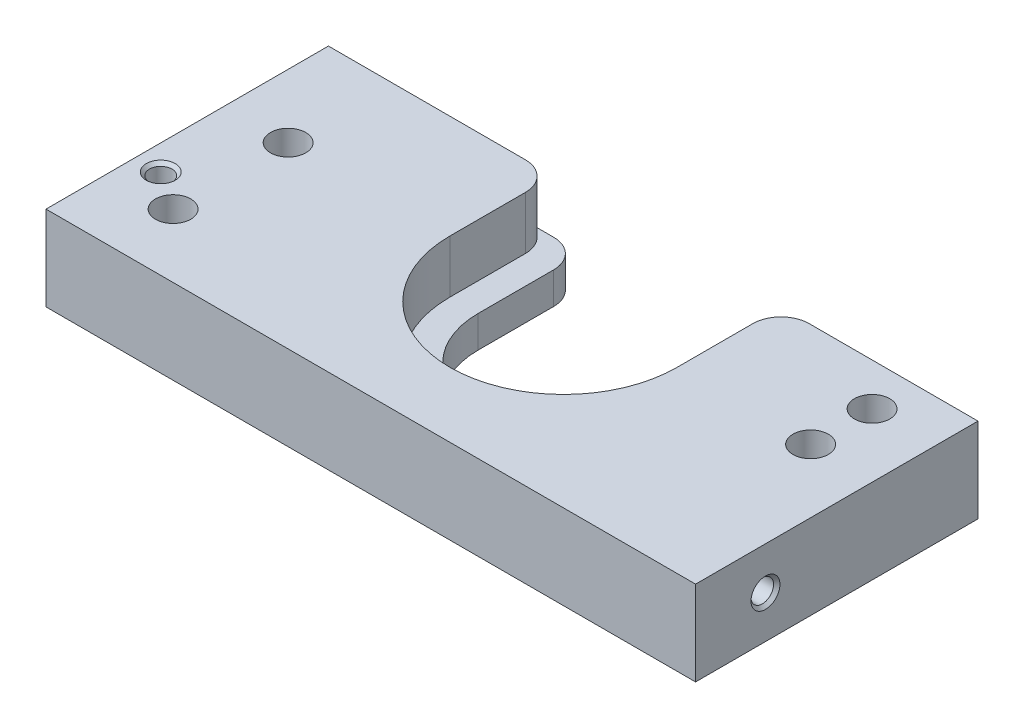
SolidWorks part; units mm, degrees
material "7075-T6, Plate (SS)"
ref_plane "Front" through (0, 0, 0) normal (0, 0, 1) x (1, 0, 0)
ref_plane "Top" through (0, 0, 0) normal (0, 1, 0) x (1, 0, 0)
ref_plane "Right" through (0, 0, 0) normal (1, 0, 0) x (0, 0, -1)
sketch "Sketch2" plane through (0, 0, 0) normal (0, 1, 0) x (1, 0, 0)
  line L6 (9.1619, -12.6472) -> (-13.4462, -12.6472)
  line L7 (20.4689, -3.3816) -> (10.4815, -12.1501)
  line L8 (6.3341, 8.3528) -> (18.8885, 4.2804)
  line L9 (-14.1784, -12.3283) -> (-22.7949, -3.0649)
  line L10 (-24, 0) -> (-24, 7.3528)
  line L11 (-23, 8.3528) -> (6.3341, 8.3528)
  line L12 (-19.5, 0) -> (17.5, 0) construction
  line L13 (0, 0) -> (0, 11.1031) construction
  arc A5 (9.1619, -12.6472) -> (10.4815, -12.1501) centre (9.1619, -10.6472) ccw
  arc A6 (20.4689, -3.3816) -> (18.8885, 4.2804) centre (17.5, 0) ccw
  arc A7 (-14.1784, -12.3283) -> (-13.4462, -12.6472) centre (-13.4462, -11.6472) ccw
  arc A8 (-24, 0) -> (-22.7949, -3.0649) centre (-19.5, 0) ccw
  arc A9 (-23, 8.3528) -> (-24, 7.3528) centre (-23, 7.3528) ccw
  circle A11 centre (-19.5, 0) radius 1.25
  circle A13 centre (0, 0) radius 2
  circle A15 centre (17.5, 0) radius 1.25
  dimension "D2" = 37
  dimension "D3" = 19.5
  dimension "D6" = 2.5
  dimension "D7" = 4
  dimension "D8" = 4.5
  dimension "D9" = 24
  dimension "D12" = 1
  dimension "D15" = 2
  dimension "D1" = 21
  dimension "D4" = 8.3528
  dimension "D5" = 17.972
  dimension "D13" = 47.072
  dimension "D14" = 41.281
sketch "Sketch1" plane through (0, 0, 0) normal (0, 1, 0) x (1, 0, 0)
  line L0 (-19.5, 0) -> (17.5, 0) construction
  line L1 (0, 0) -> (0, 6.2382) construction
  circle A0 centre (0, 0) radius 8
  dimension "D3" = 16
  dimension "D1" = 37
  dimension "D2" = 19.5
sketch "Sketch3" plane through (0, 0, 0) normal (0, 1, 0) x (1, 0, 0)
  line L1 (-24, 7.3528) -> (-8.05, 7.3528)
  line L2 (9.1619, -12.6472) -> (-13.4462, -12.6472) construction
  line L3 (22, -12.6472) -> (-24, -12.6472)
  line L4 (8.05, 7.3528) -> (22, 7.3528)
  line L5 (22, 7.3528) -> (22, -12.6472)
  line L6 (6.05, 5.3528) -> (6.05, 0)
  line L7 (-6.05, 0) -> (-6.05, 5.3528)
  line L8 (-24, -8.1472) -> (-19.5, -8.1472) construction
  line L9 (-19.5, -8.1472) -> (-19.5, -12.6472) construction
  line L13 (-24, 0) -> (-24, 7.3528) construction
  line L14 (-24, -12.6472) -> (-24, 7.3528)
  arc A1 (6.05, 0) -> (-6.05, 0) centre (0, 0) cw
  arc A3 (20.4689, -3.3816) -> (18.8885, 4.2804) centre (17.5, 0) ccw construction
  circle A5 centre (0, 0) radius 2 construction
  circle A6 centre (-19.5, -8.1472) radius 1.25
  circle A7 centre (17.5, 0) radius 1.25 construction
  circle A9 centre (17.5, 4.3528) radius 1.25
  arc A12 (8.05, 7.3528) -> (6.05, 5.3528) centre (8.05, 5.3528) ccw
  arc A13 (-6.05, 5.3528) -> (-8.05, 7.3528) centre (-8.05, 5.3528) ccw
  circle A15 centre (17.5, 0) radius 1.25
  circle A16 centre (-19.5, 0) radius 1.25 construction
  circle A17 centre (-19.5, 0) radius 1.25
  dimension "D1" = 2
  dimension "D3" = 6.05
  dimension "D5" = 2.5
  dimension "D2" = 20
  dimension "D6" = 3
extrude "Boss-Extrude1" add sketch "Sketch3" along normal blind 6
cosmetic thread "Cosmetic Thread1" parameters "D2"=3
cosmetic thread "Cosmetic Thread2" parameters "D2"=3
cosmetic thread "Cosmetic Thread3" parameters "D2"=3
cosmetic thread "Cosmetic Thread4" parameters "D2"=3
sketch "Sketch6" plane through (0, 6, 0) normal (0, 1, 0) x (1, 0, 0)
  line L0 (-8.05, 0) -> (-8.05, 5.3528)
  line L1 (-8.05, 7.3528) -> (-24, 7.3528) construction
  line L2 (-10.05, 7.3528) -> (10.05, 7.3528)
  line L3 (22, 7.3528) -> (8.05, 7.3528) construction
  line L4 (8.05, 5.3528) -> (8.05, 0)
  arc A0 (-8.05, 0) -> (8.05, 0) centre (0, 0) ccw
  arc A2 (-8.05, 5.3528) -> (-10.05, 7.3528) centre (-10.05, 5.3528) ccw
  arc A3 (10.05, 7.3528) -> (8.05, 5.3528) centre (10.05, 5.3528) ccw
  arc A4 (8.05, 7.3528) -> (6.05, 5.3528) centre (8.05, 5.3528) ccw construction
  dimension "D1" = 16.1
extrude "Cut-Extrude1" cut sketch "Sketch6" against normal blind 3.75
hole_wizard "M2 Tapped Hole1" positions "Sketch10" profile "Sketch9" tap size "M2" standard "ISO"
sketch "Sketch10" plane through (22, 0, 0) normal (1, 0, 0) x (0, 0, -1)
  line L0 (-12.6472, 6) -> (-12.6472, 0) construction
  line L1 (-12.6472, 3) -> (-7.6972, 3) construction
  point P0 (-7.6972, 3)
  dimension "D1" = 4.95
sketch "Sketch9" plane through (22, 3, 7.6972) normal (0, 1, 0) x (0, 0, -1)
  line L0 (0, 0) -> (0, 8.4807)
  line L1 (0, 8.4807) -> (0.8, 8)
  line L2 (0.8, 8) -> (0.8, 0.225)
  line L3 (0.8, 0.225) -> (1.025, 0)
  line L5 (1.025, 0) -> (0, 0)
  line L6 (-0.8, 0.225) -> (-1.025, 0) construction
  line L10 (0, 8.4807) -> (-0.8, 8) construction
  line L11 (0, -6.35) -> (0, 107.95) construction
  dimension "Tap Drill Dia." = 1.6
  dimension "Tap Drill Depth" = 8
  dimension "Near C'Sink Dia." = 2.05
  dimension "Near C'Sink Angle" = 90
  dimension "Drill Angle" = 118
cosmetic thread "Hole Thread1" parameters "D1"=6, "D2"=2
hole_wizard "M2 Tapped Hole2" positions "Sketch12" profile "Sketch11" tap size "M2" standard "ISO"
sketch "Sketch12" plane through (-24, 0, 0) normal (-1, 0, 0) x (0, 0, 1)
  line L0 (12.6472, 6) -> (12.6472, 0) construction
  line L1 (-7.3528, 6) -> (12.6472, 6) construction
  point P0 (10.5472, 3)
  dimension "D1" = 2.1
  dimension "D2" = 3
sketch "Sketch11" plane through (-24, 3, 10.5472) normal (0, 1, 0) x (0, 0, 1)
  line L0 (0, 0) -> (0, 8.4807)
  line L1 (0, 8.4807) -> (0.8, 8)
  line L2 (0.8, 8) -> (0.8, 0.225)
  line L3 (0.8, 0.225) -> (1.025, 0)
  line L5 (1.025, 0) -> (0, 0)
  line L6 (-0.8, 0.225) -> (-1.025, 0) construction
  line L10 (0, 8.4807) -> (-0.8, 8) construction
  line L11 (0, -6.35) -> (0, 107.95) construction
  dimension "Tap Drill Dia." = 1.6
  dimension "Tap Drill Depth" = 8
  dimension "Near C'Sink Dia." = 2.05
  dimension "Near C'Sink Angle" = 90
  dimension "Drill Angle" = 118
cosmetic thread "Hole Thread2" parameters "D1"=6, "D2"=2
sketch "Sketch7" [suppressed] plane through (0, 6, 0) normal (0, 1, 0) x (1, 0, 0)
  line L7 (-10.05, 7.3528) -> (-24, 7.3528)
  line L8 (-24, 7.3528) -> (-24, -12.6472)
  line L9 (-24, -12.6472) -> (22, -12.6472)
  line L10 (22, -12.6472) -> (22, 7.3528)
  line L11 (22, 7.3528) -> (10.05, 7.3528)
  line L12 (8.05, 5.3528) -> (8.05, 0)
  line L13 (-8.05, 0) -> (-8.05, 5.3528)
  line L14 (-10.05, 7.3528) -> (-24, 7.3528)
  line L15 (-24, 7.3528) -> (-24, -12.6472)
  line L16 (-24, -12.6472) -> (22, -12.6472)
  line L17 (22, -12.6472) -> (22, 7.3528)
  line L18 (22, 7.3528) -> (10.05, 7.3528)
  line L19 (8.05, 5.3528) -> (8.05, 0)
  line L20 (-8.05, 0) -> (-8.05, 5.3528)
  circle A0 centre (-19.5, 0) radius 0.75
  circle A1 centre (-19.5, -8.1472) radius 0.75
  circle A2 centre (17.5, 4.3528) radius 0.75
  arc A3 (-8.05, 5.3528) -> (-10.05, 7.3528) centre (-10.05, 5.3528) ccw
  arc A4 (10.05, 7.3528) -> (8.05, 5.3528) centre (10.05, 5.3528) ccw
  arc A5 (-8.05, 0) -> (8.05, 0) centre (0, 0) ccw
  arc A6 (-8.05, 5.3528) -> (-10.05, 7.3528) centre (-10.05, 5.3528) ccw
  arc A7 (10.05, 7.3528) -> (8.05, 5.3528) centre (10.05, 5.3528) ccw
  arc A8 (-8.05, 0) -> (8.05, 0) centre (0, 0) ccw
  circle A9 centre (17.5, 0) radius 0.75
  dimension "D2" = 1.5
  dimension "D1" = 0
extrude "Boss-Extrude2" [suppressed] add sketch "Sketch7" along normal blind 1 separate body
sketch "Sketch8" [suppressed] plane through (0, 0, 0) normal (0, -1, 0) x (1, 0, 0)
  line L7 (8.05, -7.3528) -> (22, -7.3528)
  line L8 (22, -7.3528) -> (22, 12.6472)
  line L9 (22, 12.6472) -> (-24, 12.6472)
  line L10 (-24, 12.6472) -> (-24, -7.3528)
  line L11 (-24, -7.3528) -> (-8.05, -7.3528)
  line L12 (-6.05, -5.3528) -> (-6.05, 0)
  line L13 (6.05, 0) -> (6.05, -5.3528)
  line L14 (8.05, -7.3528) -> (22, -7.3528)
  line L15 (22, -7.3528) -> (22, 12.6472)
  line L16 (22, 12.6472) -> (-24, 12.6472)
  line L17 (-24, 12.6472) -> (-24, -7.3528)
  line L18 (-24, -7.3528) -> (-8.05, -7.3528)
  line L19 (-6.05, -5.3528) -> (-6.05, 0)
  line L20 (6.05, 0) -> (6.05, -5.3528)
  circle A0 centre (-19.5, 8.1472) radius 0.75
  circle A1 centre (-19.5, 0) radius 0.75
  circle A2 centre (17.5, 0) radius 0.75
  arc A3 (6.05, -5.3528) -> (8.05, -7.3528) centre (8.05, -5.3528) ccw
  arc A4 (-8.05, -7.3528) -> (-6.05, -5.3528) centre (-8.05, -5.3528) ccw
  arc A5 (6.05, 0) -> (-6.05, 0) centre (0, 0) ccw
  arc A6 (6.05, -5.3528) -> (8.05, -7.3528) centre (8.05, -5.3528) ccw
  arc A7 (-8.05, -7.3528) -> (-6.05, -5.3528) centre (-8.05, -5.3528) ccw
  arc A8 (6.05, 0) -> (-6.05, 0) centre (0, 0) ccw
  circle A9 centre (17.5, -4.3528) radius 0.75
  dimension "D2" = 1.5
  dimension "D1" = 0
extrude "Boss-Extrude3" [suppressed] add sketch "Sketch8" along normal blind 1 separate body
hole_wizard "M2 Tapped Hole3" positions "Sketch15" profile "Sketch14" tap size "M2" standard "ISO"
sketch "Sketch15" plane through (0, 6, 0) normal (0, 1, 0) x (1, 0, 0)
  line L0 (-24, 7.3528) -> (-24, -12.6472) construction
  line L1 (-24, -12.6472) -> (22, -12.6472) construction
  point P0 (-22.217, -6.3042)
  dimension "D1" = 1.783
  dimension "D2" = 6.343
sketch "Sketch14" plane through (-22.217, 6, 6.3042) normal (1, 0, 0) x (0, 0, 1)
  line L0 (0, 0) -> (0, 6.4807)
  line L1 (0, 6.4807) -> (0.8, 6)
  line L2 (0.8, 6) -> (0.8, 0.225)
  line L3 (0.8, 0.225) -> (1.025, 0)
  line L5 (1.025, 0) -> (0, 0)
  line L6 (-0.8, 0.225) -> (-1.025, 0) construction
  line L10 (0, 6.4807) -> (-0.8, 6) construction
  line L11 (0, -6.35) -> (0, 107.95) construction
  dimension "Tap Drill Dia." = 1.6
  dimension "Tap Drill Depth" = 6
  dimension "Near C'Sink Dia." = 2.05
  dimension "Near C'Sink Angle" = 90
  dimension "Drill Angle" = 118
cosmetic thread "Hole Thread3" parameters "D1"=4, "D2"=2
